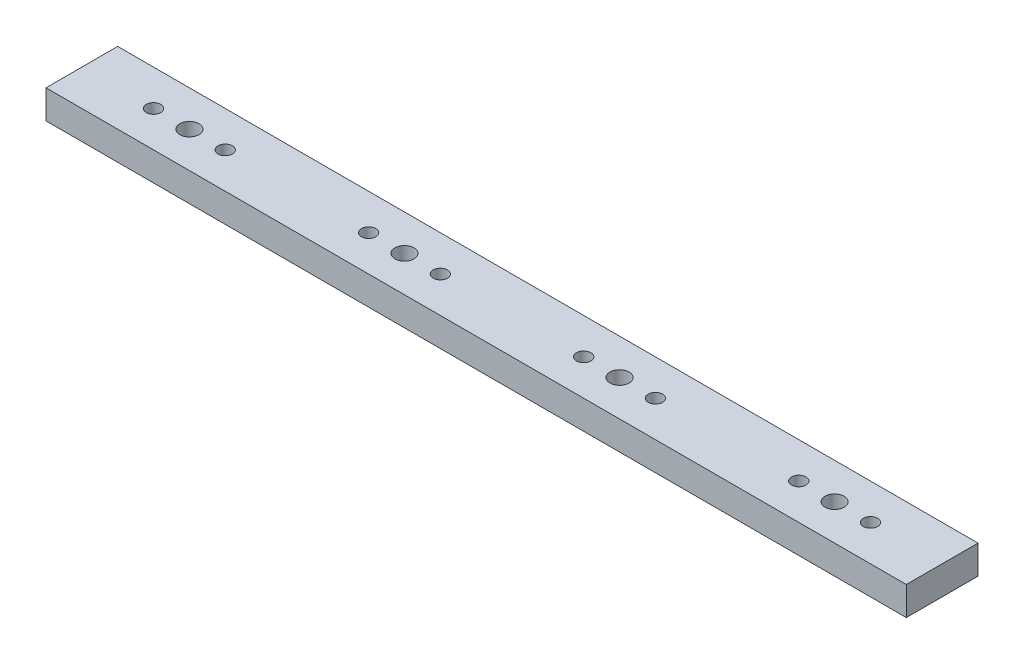
SolidWorks part; units mm, degrees
material "Beech"
ref_plane "Front Plane" through (0, 0, 0) normal (0, 0, 1) x (1, 0, 0)
ref_plane "Top Plane" through (0, 0, 0) normal (0, 1, 0) x (1, 0, 0)
ref_plane "Right Plane" through (0, 0, 0) normal (1, 0, 0) x (0, 0, -1)
sketch "Sketch1" plane through (0, 0, 0) normal (0, 1, 0) x (1, 0, 0)
  line L1 (-180, -15) -> (180, -15)
  line L2 (-180, -15) -> (-180, 15)
  line L3 (-180, 15) -> (180, 15)
  line L4 (180, -15) -> (180, 15)
  line L5 (-180, -15) -> (180, 15) construction
  line L6 (-180, 15) -> (180, -15) construction
  point P0 (0, 0)
extrude "Boss-Extrude1" add sketch "Sketch1" along normal blind 12
sketch "Sketch2" plane through (0, 12, 0) normal (0, 1, 0) x (1, 0, 0)
  line L0 (-180, 15) -> (-180, -15) construction
  circle A0 centre (-150, 0) radius 3
  circle A1 centre (-120, 0) radius 3
  circle A2 centre (-135, 0) radius 4
  dimension "D1" = 6
  dimension "D3" = 6
  dimension "D5" = 8
  dimension "D2" = 30
  dimension "D4" = 60
  dimension "D6" = 15
extrude "Cut-Extrude1" cut sketch "Sketch2" against normal up to next
pattern_linear "LPattern1" count 4 spacing 90 along (1, 0, 0) of "Cut-Extrude1"
